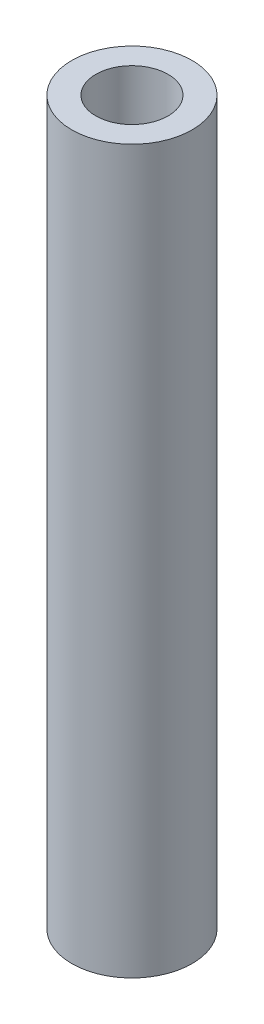
SolidWorks part; units mm, degrees
ref_plane "Front Plane" through (0, 0, 0) normal (0, 0, 1) x (1, 0, 0)
ref_plane "Top Plane" through (0, 0, 0) normal (0, 1, 0) x (1, 0, 0)
ref_plane "Right Plane" through (0, 0, 0) normal (1, 0, 0) x (0, 0, -1)
sketch "Sketch1" plane through (0, 0, 0) normal (0, 1, 0) x (1, 0, 0)
  circle A0 centre (0, 0) radius 2.5
  circle A1 centre (0, 0) radius 1.5
  dimension "D1" = 5
  dimension "D2" = 3
extrude "Boss-Extrude1" add sketch "Sketch1" along normal mid plane 30
ref_point "Point1"
move or copy body "Body-Move/Copy1" [suppressed] bodies to move or copy 101
